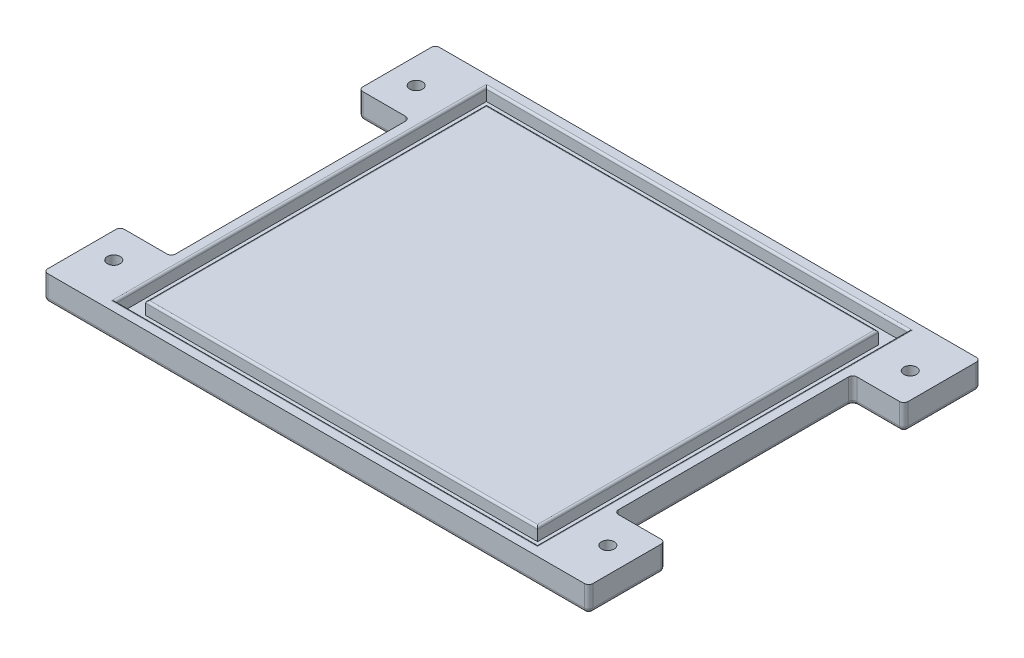
SolidWorks part; units mm, degrees
ref_plane "Plano frontal" through (0, 0, 0) normal (0, 0, 1) x (1, 0, 0)
ref_plane "Plano superior" through (0, 0, 0) normal (0, 1, 0) x (1, 0, 0)
ref_plane "Plano direito" through (0, 0, 0) normal (1, 0, 0) x (0, 0, -1)
sketch "Esboço1" plane through (0, 0, 0) normal (0, 1, 0) x (1, 0, 0)
  line L1 (0, 0) -> (-104, 0)
  line L2 (0, 0) -> (0, 92)
  line L3 (0, 92) -> (-104, 92)
  line L4 (-104, 0) -> (-104, 92)
  dimension "D1" = 92
  dimension "D2" = 104
extrude "Ressalto-extrusão1" add sketch "Esboço1" along normal blind 6
sketch "Esboço2" plane through (0, 6, 0) normal (0, 1, 0) x (1, 0, 0)
  line L9 (-101.5, 89.5) -> (-2.5, 89.5)
  line L10 (-101.5, 89.5) -> (-101.5, 2.5)
  line L11 (-101.5, 2.5) -> (-2.5, 2.5)
  line L12 (-2.5, 89.5) -> (-2.5, 2.5)
  line L13 (-101.5, 89.5) -> (-98, 89.5)
  line L14 (-101.5, 89.5) -> (-101.5, 86)
  line L17 (-2.5, 2.5) -> (-6, 2.5)
  line L18 (-2.5, 2.5) -> (-2.5, 6)
  line L21 (-6, 6) -> (-98, 6)
  line L22 (-6, 6) -> (-6, 86)
  line L23 (-6, 86) -> (-98, 86)
  line L24 (-98, 6) -> (-98, 86)
extrude "Corte-extrusão1" cut sketch "Esboço2" against normal blind 3 contours L12 L9 L10 L11 L21 L24 L23 L22
fillet "Filete1" radius 0.5 8 edges at (-52, 6, -89.5) (-52, 6, -86) (-101.5, 6, -46) (-98, 6, -46) (-52, 6, -6) (-52, 6, -2.5) (-6, 6, -46) (-2.5, 6, -46)
sketch "Esboço4" plane through (0, 6, 0) normal (0, 1, 0) x (1, 0, 0)
  line L1 (-104, 92) -> (-116, 92)
  line L2 (-104, 92) -> (-104, 77)
  line L3 (-104, 77) -> (-116, 77)
  line L4 (-116, 92) -> (-116, 77)
  line L5 (-104, 0) -> (-116, 0)
  line L6 (-104, 0) -> (-104, 15)
  line L7 (-104, 15) -> (-116, 15)
  line L8 (-116, 0) -> (-116, 15)
  line L9 (0, 92) -> (12, 92)
  line L10 (0, 92) -> (0, 77)
  line L11 (0, 77) -> (12, 77)
  line L12 (12, 92) -> (12, 77)
  line L13 (0, 0) -> (12, 0)
  line L14 (0, 0) -> (0, 15)
  line L15 (0, 15) -> (12, 15)
  line L16 (12, 0) -> (12, 15)
  dimension "D1" = 12
  dimension "D2" = 15
  dimension "D3" = 15
  dimension "D4" = 12
  dimension "D5" = 12
  dimension "D6" = 15
  dimension "D7" = 12
  dimension "D8" = 15
extrude "Ressalto-extrusão2" add sketch "Esboço4" against normal blind 6
sketch "Esboço5" plane through (0, 6, 0) normal (0, 1, 0) x (1, 0, 0)
  circle A0 centre (-110, 84.5) radius 1.5
  circle A1 centre (6, 84.5) radius 1.5
  circle A2 centre (6, 7.5) radius 1.5
  circle A3 centre (-110, 7.5) radius 1.5
extrude "Corte-extrusão2" cut sketch "Esboço5" against normal blind 6
sketch "Esboço6" plane through (0, 0, 0) normal (0, -1, 0) x (1, 0, 0)
  circle A0 centre (-110, -7.5) radius 2.5
  circle A1 centre (6, -7.5) radius 2.5
  circle A2 centre (6, -84.5) radius 2.5
  circle A3 centre (-110, -84.5) radius 2.5
  dimension "D1" = 5
  dimension "D2" = 5
  dimension "D3" = 5
  dimension "D4" = 5
extrude "Corte-extrusão3" cut sketch "Esboço6" against normal blind 2
sketch "Esboço7" plane through (0, 6, 0) normal (0, 1, 0) x (1, 0, 0)
  line L1 (1.3177, 89.4069) -> (9.298, 89.4069)
  line L2 (1.3177, 89.4069) -> (1.3177, 80.3048)
  line L3 (1.3177, 80.3048) -> (9.298, 80.3048)
  line L4 (9.298, 89.4069) -> (9.298, 80.3048)
  line L5 (-113.4658, 89.4069) -> (-106.8694, 89.4069)
  line L6 (-113.4658, 89.4069) -> (-113.4658, 79.0473)
  line L7 (-113.4658, 79.0473) -> (-106.8694, 79.0473)
  line L8 (-106.8694, 89.4069) -> (-106.8694, 79.0473)
  line L9 (-113.4658, 12.0538) -> (-106.8694, 12.0538)
  line L10 (-113.4658, 12.0538) -> (-113.4658, 2.0511)
  line L11 (-113.4658, 2.0511) -> (-106.8694, 2.0511)
  line L12 (-106.8694, 12.0538) -> (-106.8694, 2.0511)
  line L13 (3.1387, 12.0538) -> (9.298, 12.0538)
  line L14 (3.1387, 12.0538) -> (3.1387, 3.5192)
  line L15 (3.1387, 3.5192) -> (9.298, 3.5192)
  line L16 (9.298, 12.0538) -> (9.298, 3.5192)
extrude "Ressalto-extrusão3" add sketch "Esboço7" against normal blind 6
sketch "Esboço8" plane through (0, 0, 0) normal (0, -1, 0) x (1, 0, 0)
  line L1 (5.7224, -10.6654) -> (0.6177, -10.6654)
  line L2 (5.7224, -10.6654) -> (5.7224, -4.9375)
  line L3 (5.7224, -4.9375) -> (0.6177, -4.9375)
  line L4 (0.6177, -10.6654) -> (0.6177, -4.9375)
extrude "Ressalto-extrusão4" add sketch "Esboço8" against normal blind 6
sketch "Esboço9" plane through (0, 0, 0) normal (0, -1, 0) x (-1, 0, 0)
  line L0 (104, 77) -> (104, 15) construction
  line L1 (116, 92) -> (104, 92)
  line L2 (116, 92) -> (116, 74)
  line L3 (116, 74) -> (104, 74)
  line L4 (104, 92) -> (104, 74)
  line L5 (-12, 77) -> (-12, 92) construction
  line L6 (-12, 92) -> (0, 92)
  line L7 (-12, 92) -> (-12, 74)
  line L8 (-12, 74) -> (0, 74)
  line L9 (0, 92) -> (0, 74)
  line L10 (-12, 92) -> (116, 92) construction
  line L11 (0, 15) -> (0, 77) construction
  line L13 (116, 0) -> (104, 0)
  line L14 (116, 0) -> (116, 18)
  line L15 (116, 18) -> (104, 18)
  line L16 (104, 0) -> (104, 18)
  line L17 (-12, 0) -> (0, 0)
  line L18 (-12, 0) -> (-12, 18)
  line L19 (-12, 18) -> (0, 18)
  line L20 (0, 0) -> (0, 18)
  dimension "D1" = 18
  dimension "D2" = 18
  dimension "D3" = 18
  dimension "D4" = 18
extrude "Ressalto-extrusão6" add sketch "Esboço9" against normal blind 6
sketch "Esboço10" plane through (0, 0, 0) normal (0, -1, 0) x (1, 0, 0)
  line L0 (-116, 0) -> (-116, -10.5)
  line L1 (-116, -18) -> (-116, 0) construction
  line L2 (-116, -10.5) -> (-110, -10.5)
  circle A0 centre (-110, -10.5) radius 1.5
  dimension "D3" = 3
  dimension "D1" = 10.5
  dimension "D2" = 6
extrude "Corte-extrusão5" cut sketch "Esboço10" against normal blind 10
sketch "Esboço11" plane through (0, 6, 0) normal (0, 1, 0) x (1, 0, 0)
  circle A0 centre (-110, 81.5) radius 1.5
  circle A1 centre (6, 81.5) radius 1.5
  circle A2 centre (6, 10.5) radius 1.5
extrude "Corte-extrusão6" cut sketch "Esboço11" against normal blind 10
fillet "Filete8" radius 1 28 edges at (-104, 3, -18) (-116, 3, -18) (-116, 3, 0) (-104, 3, -74) (-110, 0, -74) (-116, 3, -74) (-110, 0, -80) (-116, 0, -83) (-116, 3, -92) (12, 3, -92) (0, 3, -18) (12, 3, -18) (12, 3, 0) (0, 3, -74) (12, 3, -74) (-52, 0, -92) (6, 0, -80) (6, 0, -74) (12, 0, -83) (6, 0, -18) (6, 0, -9) (12, 0, -9) (-110, 0, -18) (-116, 0, -9) (-110, 0, -12) (-52, 0, 0)
